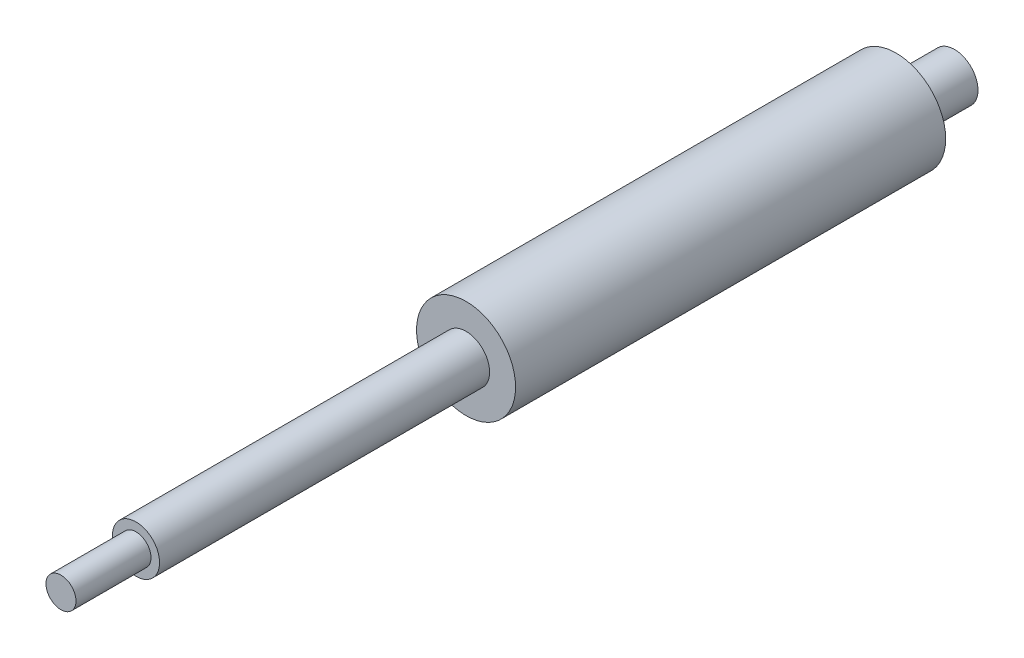
SolidWorks part; units mm, degrees
material "4032-T6"
ref_plane "Front Plane" through (0, 0, 0) normal (0, 0, 1) x (1, 0, 0)
ref_plane "Top Plane" through (0, 0, 0) normal (0, 1, 0) x (1, 0, 0)
ref_plane "Right Plane" through (0, 0, 0) normal (1, 0, 0) x (0, 0, -1)
sketch "Sketch1" plane through (0, 0, 0) normal (0, 0, 1) x (1, 0, 0)
  circle A0 centre (0, 0) radius 9.9
  dimension "D1" = 19.8
extrude "Boss-Extrude1" add sketch "Sketch1" along normal blind 86
sketch "Sketch3" plane through (0, 0, 86) normal (0, 0, 1) x (1, 0, 0)
  circle A0 centre (0, 0) radius 4.7125
  dimension "D1" = 9.425
extrude "Boss-Extrude3" add sketch "Sketch3" along normal blind 66 and the other way blind 97.65
sketch "Sketch2" plane through (0, 0, 86) normal (0, 0, 1) x (1, 0, 0)
  circle A0 centre (0, 0) radius 3
extrude "Boss-Extrude2" add sketch "Sketch2" along normal blind 15 from offset 66
